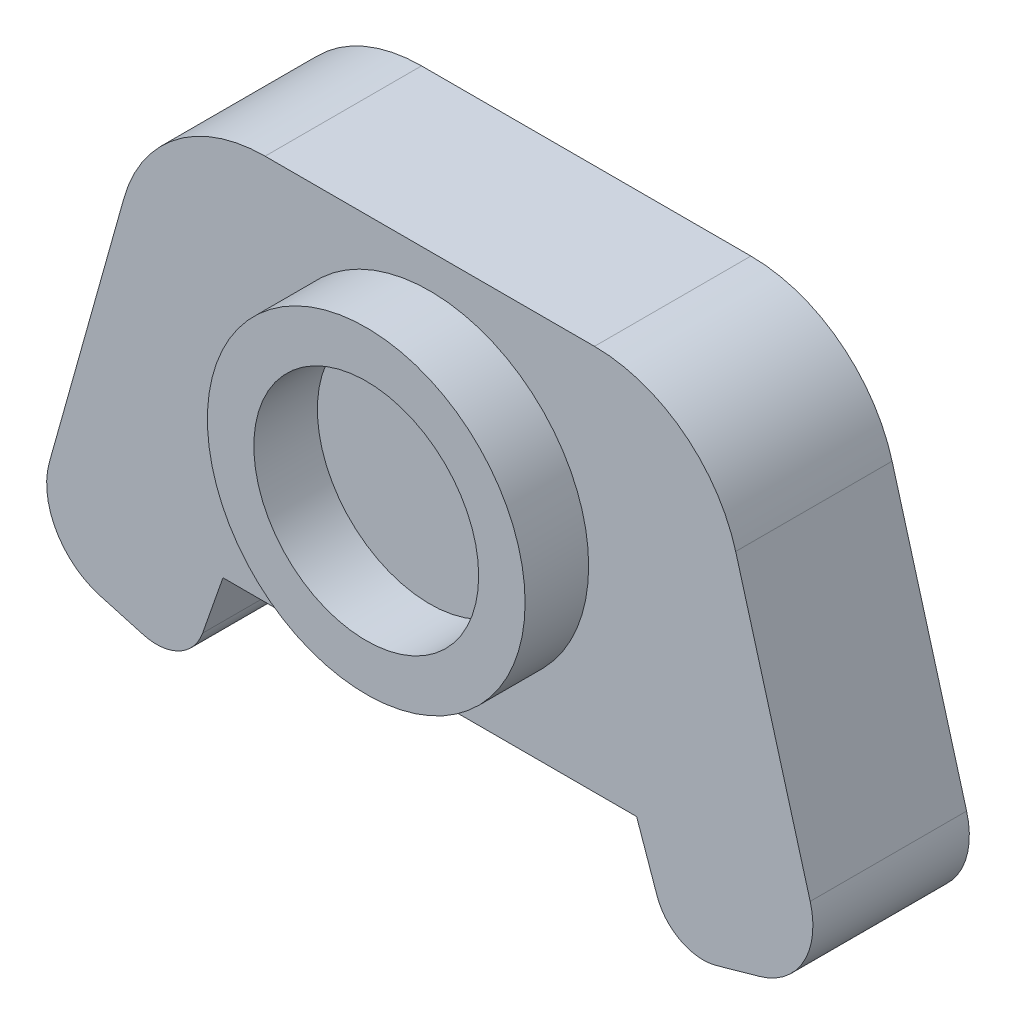
SolidWorks part; units mm, degrees
ref_plane "Front Plane" through (0, 0, 0) normal (0, 0, 1) x (1, 0, 0)
ref_plane "Top Plane" through (0, 0, 0) normal (0, 1, 0) x (1, 0, 0)
ref_plane "Right Plane" through (0, 0, 0) normal (1, 0, 0) x (0, 0, -1)
sketch "Sketch2" plane through (0, 0, 0) normal (0, 0, 1) x (1, 0, 0)
  line L0 (-5.6438, 3.5188) -> (5.6438, 3.5188)
  line L1 (5.6438, 3.5188) -> (8.1872, -5.5523)
  line L2 (8.1872, -5.5523) -> (4.9581, -6.4577)
  line L3 (4.9581, -6.4577) -> (4.2312, -4.3812)
  line L4 (4.2312, -4.3812) -> (-4.2312, -4.3812)
  line L6 (0, 3.5188) -> (0, 7.4063) construction
  line L7 (-4.9581, -6.4577) -> (-4.2312, -4.3812)
  line L8 (-8.1872, -5.5523) -> (-4.9581, -6.4577)
  line L9 (-5.6438, 3.5188) -> (-8.1872, -5.5523)
  dimension "D2" = 2.2
extrude "Boss-Extrude1" add sketch "Sketch2" along normal blind 3.2
ref_plane "Plane1" through (0, 0, 3.2) normal (0, 0, 1) x (1, 0, 0)
sketch "Sketch3" plane through (0, 0, 3.2) normal (0, 0, 1) x (1, 0, 0)
  line L0 (0, 3.5188) -> (0, -4.3812) construction
  line L1 (5.6438, 3.5188) -> (-5.6438, 3.5188) construction
  line L2 (-4.2312, -4.3812) -> (4.2312, -4.3812) construction
  circle A0 centre (0, -0.4312) radius 3.25
  circle A1 centre (0, -0.4312) radius 2.3
  dimension "D1" = 6.5
  dimension "D2" = 4.6
extrude "Boss-Extrude2" add sketch "Sketch3" along normal blind 1.3
fillet "Fillet1" radius 3 2 edges at (-5.6438, 3.5188, 1.6) (5.6438, 3.5188, 1.6)
fillet "Fillet2" radius 1.5 2 edges at (-8.1872, -5.5523, 1.6) (8.1872, -5.5523, 1.6)
fillet "Fillet3" radius 1 2 edges at (-4.9581, -6.4577, 1.6) (4.9581, -6.4577, 1.6)
